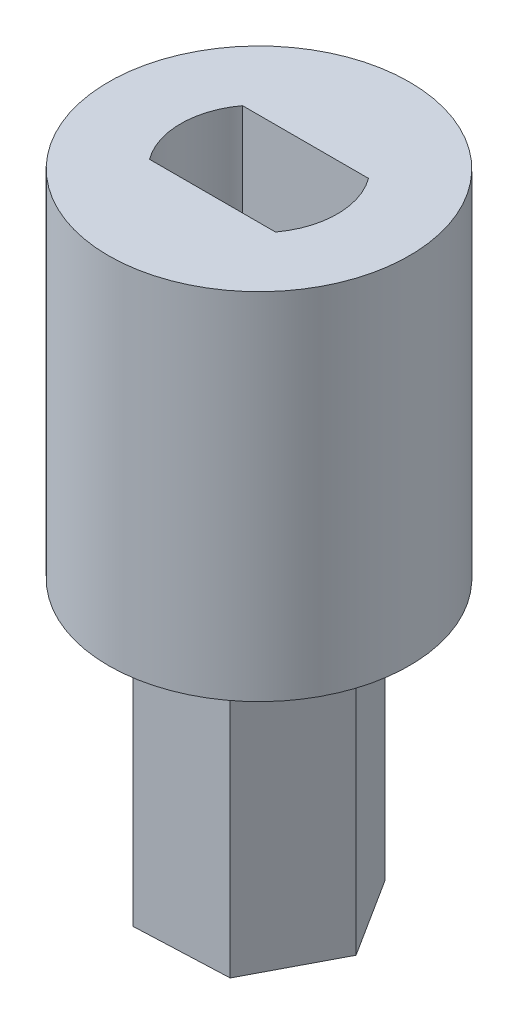
SolidWorks part; units mm, degrees
ref_plane "Alzado" through (0, 0, 0) normal (0, 0, 1) x (1, 0, 0)
ref_plane "Planta" through (0, 0, 0) normal (0, 1, 0) x (1, 0, 0)
ref_plane "Vista lateral" through (0, 0, 0) normal (1, 0, 0) x (0, 0, -1)
sketch "Croquis1" plane through (0, 0, 0) normal (0, 1, 0) x (1, 0, 0)
  line L1 (2.0413, -3.2176) -> (3.8072, 0.159)
  line L2 (3.8072, 0.159) -> (1.7659, 3.3766)
  line L3 (1.7659, 3.3766) -> (-2.0413, 3.2176)
  line L4 (-2.0413, 3.2176) -> (-3.8072, -0.159)
  line L5 (-3.8072, -0.159) -> (-1.7659, -3.3766)
  line L6 (-1.7659, -3.3766) -> (2.0413, -3.2176)
  circle A0 centre (0, 0) radius 3.3 construction
  dimension "D1" = 3.3
extrude "Saliente-Extruir1" add sketch "Croquis1" along normal blind 11.5
sketch "Croquis2" plane through (0, 11.5, 0) normal (0, 1, 0) x (1, 0, 0)
  circle A0 centre (0, 0) radius 6.15
  dimension "D1" = 12.3
extrude "Saliente-Extruir2" add sketch "Croquis2" along normal blind 14.51
sketch "Croquis3" plane through (0, 0, 0) normal (0, -1, 0) x (1, 0, 0)
  circle A0 centre (0, 0) radius 1.25
  dimension "D1" = 2.5
extrude "Cortar-Extruir1" cut sketch "Croquis3" against normal blind 8 contours A0
sketch "Croquis4" plane through (0, 26.01, 0) normal (0, 1, 0) x (1, 0, 0)
  line L1 (-2.5749, 1.9) -> (2.5749, 1.9)
  line L3 (-2.5749, -1.9) -> (2.5749, -1.9)
  line L5 (-2.5749, 1.9) -> (2.5749, -1.9) construction
  line L6 (-2.5749, -1.9) -> (2.5749, 1.9) construction
  arc A0 (-2.5749, 1.9) -> (-2.5749, -1.9) centre (0, 0) ccw
  arc A1 (2.5749, -1.9) -> (2.5749, 1.9) centre (0, 0) ccw
  dimension "D1" = 3.8
  dimension "D2" = 6.4
extrude "Cortar-Extruir2" cut sketch "Croquis4" against normal blind 8
